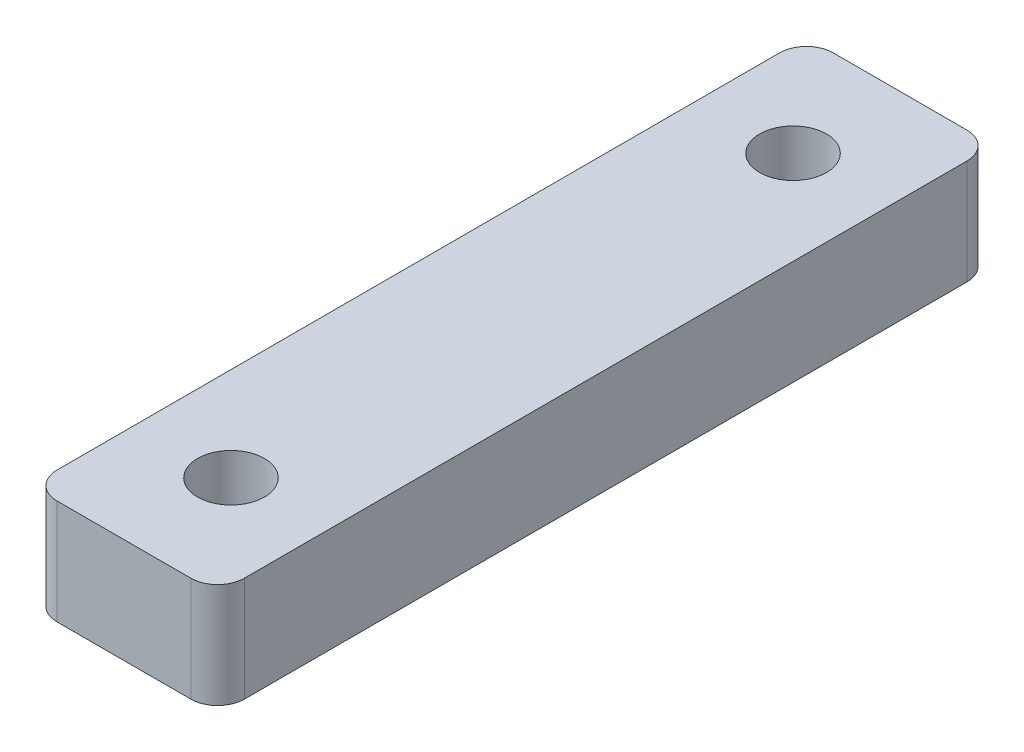
SolidWorks part; units mm, degrees
ref_plane "Front Plane" through (0, 0, 0) normal (0, 0, 1) x (1, 0, 0)
ref_plane "Top Plane" through (0, 0, 0) normal (0, 1, 0) x (1, 0, 0)
ref_plane "Right Plane" through (0, 0, 0) normal (1, 0, 0) x (0, 0, -1)
sketch "Sketch1" plane through (0, 0, 0) normal (0, 1, 0) x (1, 0, 0)
  line L0 (7, 58) -> (7, 0) construction
  line L1 (0, 0) -> (14, 0)
  line L2 (0, 0) -> (0, 58)
  line L3 (0, 58) -> (14, 58)
  line L4 (14, 0) -> (14, 58)
  line L5 (0, 29) -> (14, 29) construction
  circle A0 centre (7, 50) radius 2.5
  circle A1 centre (7, 8) radius 2.5
  dimension "D4" = 5
  dimension "D1" = 58
  dimension "D2" = 14
  dimension "D3" = 42
extrude "Boss-Extrude1" add sketch "Sketch1" along normal blind 7.83 contours L1 L4 L3 L2 A0 A1
fillet "Fillet1" radius 2 4 edges at (14, 3.915, 0) (0, 3.915, 0) (14, 3.915, -58) (0, 3.915, -58)
